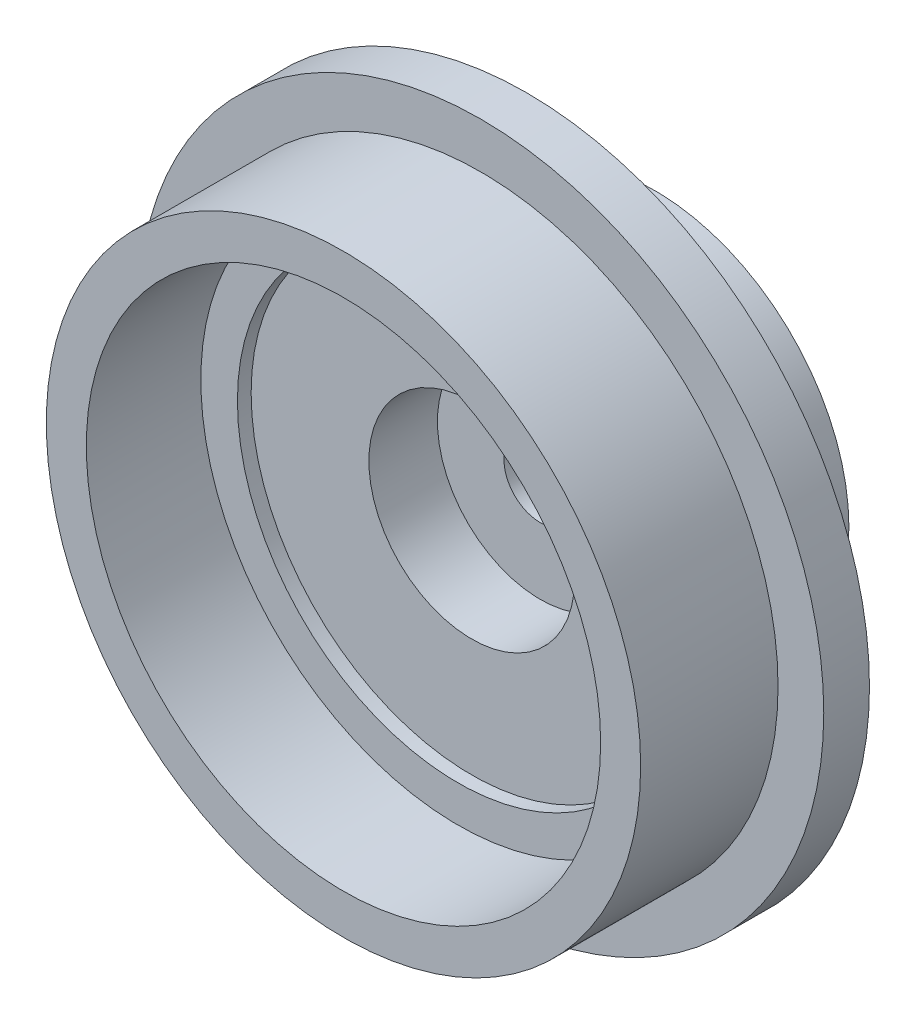
SolidWorks part; units mm, degrees
material "6061-T6 (SS)"
ref_plane "Front Plane" through (0, 0, 0) normal (0, 0, 1) x (1, 0, 0)
ref_plane "Top Plane" through (0, 0, 0) normal (0, 1, 0) x (1, 0, 0)
ref_plane "Right Plane" through (0, 0, 0) normal (1, 0, 0) x (0, 0, -1)
sketch "Sketch1" plane through (0, 0, 0) normal (1, 0, 0) x (0, 0, -1)
  line L0 (-32.3517, 0) -> (72.8588, 0) construction
  line L1 (17.2847, 0) -> (7.1247, 0)
  line L2 (7.1247, 0) -> (7.1247, 12.2555)
  line L3 (7.1247, 12.2555) -> (6.3627, 12.2555)
  line L4 (6.3627, 12.2555) -> (6.3627, 14.2875)
  line L5 (6.3627, 14.2875) -> (0, 14.2875)
  line L6 (0, 14.2875) -> (0, 16.51)
  line L7 (0, 16.51) -> (7.6327, 16.51)
  line L8 (10.1727, 19.05) -> (10.1727, 10.795)
  line L9 (10.1727, 10.795) -> (17.2847, 10.795)
  line L10 (17.2847, 10.795) -> (17.2847, 0)
  line L11 (7.6327, 16.51) -> (7.6327, 19.05)
  line L12 (7.6327, 19.05) -> (10.1727, 19.05)
  dimension "D1" = 28.575
  dimension "D2" = 33.02
  dimension "D3" = 6.3627
  dimension "D4" = 2.032
  dimension "D5" = 0.762
  dimension "D6" = 3.81
  dimension "D7" = 21.59
  dimension "D8" = 7.112
  dimension "D9" = 38.1
  dimension "D10" = 2.54
revolve "Revolve1" add sketch "Sketch1" angle 360 about L0
sketch "Sketch2" plane through (0, 0, -7.1247) normal (0, 0, 1) x (1, 0, 0)
  circle A0 centre (0, 0) radius 2.0193
  dimension "D1" = 4.0386
extrude "Cut-Extrude1" cut sketch "Sketch2" against normal through all
sketch "Sketch3" plane through (0, 0, -7.1247) normal (0, 0, 1) x (1, 0, 0)
  circle A0 centre (0, 0) radius 5.715
  dimension "D1" = 11.43
extrude "Cut-Extrude2" cut sketch "Sketch3" against normal blind 3.81
